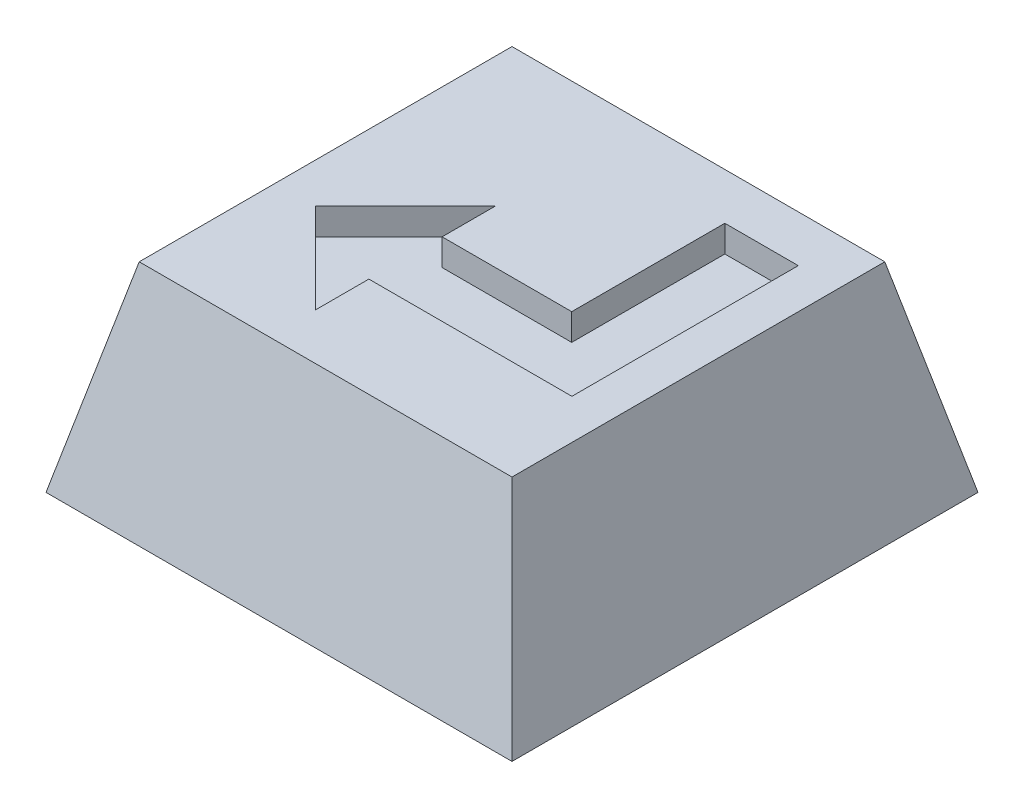
SolidWorks part; units mm, degrees
ref_plane "Front Plane" through (0, 0, 0) normal (0, 0, 1) x (1, 0, 0)
ref_plane "Top Plane" through (0, 0, 0) normal (0, 1, 0) x (1, 0, 0)
ref_plane "Right Plane" through (0, 0, 0) normal (1, 0, 0) x (0, 0, -1)
sketch "Sketch1" plane through (0, 0, 0) normal (0, 1, 0) x (1, 0, 0)
  line L1 (0, 0) -> (7, 0)
  line L2 (0, 0) -> (0, 7)
  line L3 (0, 7) -> (7, 7)
  line L4 (7, 0) -> (7, 7)
  dimension "D1" = 7
  dimension "D2" = 7
extrude "Boss-Extrude1" add sketch "Sketch1" along normal blind 3
sketch "Sketch2" plane through (0, 0, 0) normal (0, 0, 1) x (1, 0, 0)
  line L0 (0, 0) -> (0.7, 3)
  line L1 (0, 3) -> (7, 3) construction
  line L2 (0.7, 3) -> (0, 3)
  line L3 (0, 3) -> (0, 0)
  line L4 (7, 0) -> (6.3, 3)
  line L5 (6.3, 3) -> (7, 3)
  line L6 (7, 3) -> (7, 0)
  dimension "D1" = 0.7
  dimension "D2" = 0.7
extrude "Cut-Extrude1" cut sketch "Sketch2" against normal blind 7
sketch "Sketch3" plane through (0, 0, 0) normal (1, 0, 0) x (0, 0, -1)
  line L0 (0, 0) -> (0.7, 3)
  line L1 (7, 3) -> (0, 3) construction
  line L2 (0.7, 3) -> (0, 3)
  line L3 (0, 3) -> (0, 0)
  line L4 (7, 3) -> (6.3, 3)
  line L5 (6.3, 3) -> (7, 0)
  line L6 (7, 3) -> (7, 0)
  dimension "D1" = 0.7
  dimension "D2" = 0.7
extrude "Cut-Extrude2" cut sketch "Sketch3" along normal blind 11
sketch "Sketch4" plane through (0, 0, 0) normal (0, -1, 0) x (1, 0, 0)
  line L0 (3.5, 0) -> (3.5, -7) construction
  line L1 (0, 0) -> (7, 0) construction
  line L2 (7, -7) -> (0, -7) construction
  line L3 (0, -3.5) -> (7, -3.5) construction
  line L4 (0, -7) -> (0, 0) construction
  line L5 (7, 0) -> (7, -7) construction
  circle A0 centre (3.5, -3.5) radius 1.8
  dimension "D1" = 3.6
extrude "Cut-Extrude3" cut sketch "Sketch4" against normal blind 0.8
sketch "Sketch5" plane through (0, 3, 0) normal (0, 1, 0) x (1, 0, 0)
  line L0 (2.65, 3.3) -> (2.65, 4.1)
  line L1 (4.5971, 5.6) -> (5.7, 5.6)
  line L2 (4.5971, 5.6) -> (4.5971, 2.2)
  line L3 (4.5971, 2.2) -> (5.7, 2.2)
  line L4 (5.7, 5.6) -> (5.7, 2.2)
  line L5 (4.5971, 2.2) -> (2.65, 2.2)
  line L6 (4.5971, 2.2) -> (4.5971, 3.3)
  line L7 (4.5971, 3.3) -> (2.65, 3.3)
  line L8 (2.65, 2.2) -> (2.65, 3.3)
  line L9 (2.65, 4.1) -> (1.3, 2.75)
  line L10 (1.3, 2.75) -> (2.65, 1.4)
  line L11 (2.65, 1.4) -> (2.65, 2.2)
  line L12 (0.7, 6.3) -> (0.7, 0.7) construction
  line L13 (6.3, 6.3) -> (6.3, 0.7) construction
  line L14 (6.3, 6.3) -> (0.7, 6.3) construction
  line L15 (6.3, 0.7) -> (0.7, 0.7) construction
  dimension "D1" = 0.6
  dimension "D2" = 0.6
  dimension "D3" = 0.7
  dimension "D4" = 0.8
  dimension "D5" = 0.8
  dimension "D6" = 1.1
  dimension "D7" = 1.1029
  dimension "D8" = 0.7
extrude "Cut-Extrude4" cut sketch "Sketch5" against normal blind 0.4 contours L10 L11 L8 L0 L9 | L8 L5 L2 L7 | L4 L1 L2 L3
